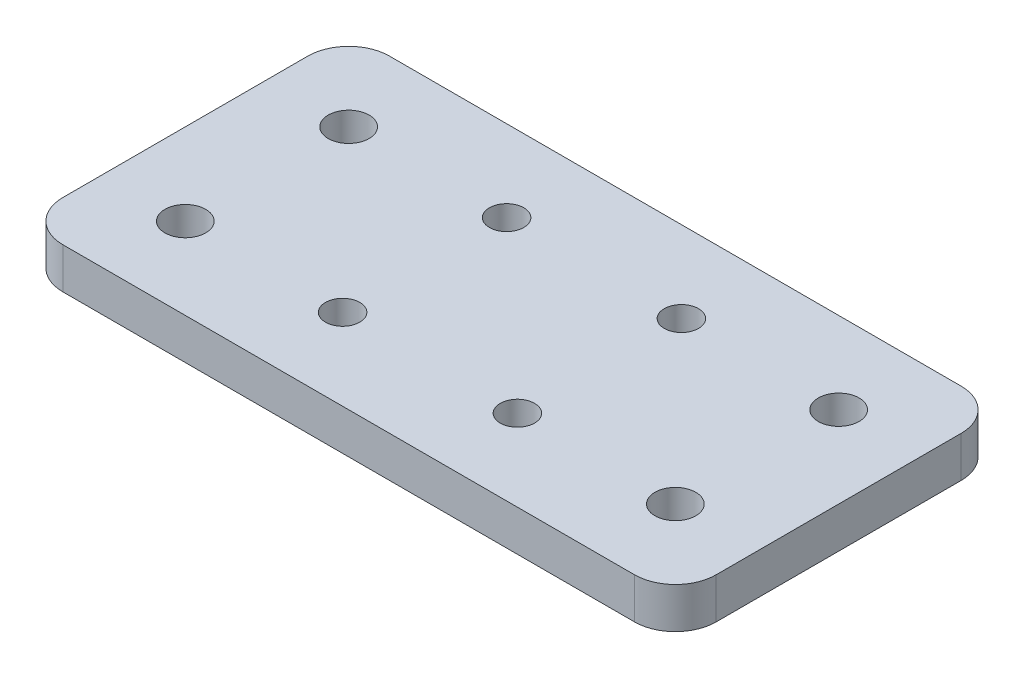
SolidWorks part; units mm, degrees
material "6061 Alloy"
ref_plane "Front Plane" through (0, 0, 0) normal (0, 0, 1) x (1, 0, 0)
ref_plane "Top Plane" through (0, 0, 0) normal (0, 1, 0) x (1, 0, 0)
ref_plane "Right Plane" through (0, 0, 0) normal (1, 0, 0) x (0, 0, -1)
sketch "Sketch1" plane through (0, 0, 0) normal (0, 1, 0) x (1, 0, 0)
  line L1 (-50.8, 25.4) -> (50.8, 25.4)
  line L2 (-50.8, 25.4) -> (-50.8, -25.4)
  line L3 (-50.8, -25.4) -> (50.8, -25.4)
  line L4 (50.8, 25.4) -> (50.8, -25.4)
  line L5 (-50.8, 25.4) -> (50.8, -25.4) construction
  line L6 (-50.8, -25.4) -> (50.8, 25.4) construction
  point P0 (0, 0)
  dimension "D1" = 50.8
  dimension "D2" = 101.6
extrude "Boss-Extrude1" add sketch "Sketch1" along normal blind 6.35
sketch "Sketch3" plane through (0, 0, 0) normal (0, -1, 0) x (1, 0, 0)
  line L0 (0, 0) -> (0, -20.7585) construction
  line L1 (1.5, 0) -> (-11.6006, 0) construction
  line L6 (50.8, -25.4) -> (-50.8, -25.4) construction
  line L7 (-50.8, 25.4) -> (50.8, 25.4) construction
  line L8 (-50.8, -25.4) -> (-50.8, 25.4) construction
  line L9 (50.8, 25.4) -> (50.8, -25.4) construction
  circle A0 centre (-38.1, 12.7) radius 3.175
  circle A1 centre (-38.1, -12.7) radius 3.175
  circle A2 centre (38.1, 12.7) radius 3.175
  circle A3 centre (38.1, -12.7) radius 3.175
  circle A4 centre (13.589, -12.75) radius 2.667
  circle A5 centre (-13.589, -12.75) radius 2.667
  circle A6 centre (13.589, 12.75) radius 2.667
  circle A7 centre (-13.589, 12.75) radius 2.667
  dimension "D1" = 25.4
  dimension "D4" = 50.8
  dimension "D5" = 13.589
  dimension "D6" = 13.589
  dimension "D7" = 13.589
  dimension "D8" = 13.589
  dimension "D9" = 12.75
  dimension "D10" = 12.75
  dimension "D11" = 12.75
  dimension "D13" = 5.334
  dimension "D3" = 50.8
  dimension "D14" = 5.334
  dimension "D15" = 5.334
  dimension "D16" = 5.334
  dimension "D17" = 6.35
  dimension "D18" = 6.35
  dimension "D19" = 6.35
  dimension "D20" = 6.35
  dimension "D21" = 12.7
  dimension "D22" = 12.7
  dimension "D23" = 12.7
  dimension "D24" = 12.7
  dimension "D26" = 12.7
  dimension "D27" = 12.7
  dimension "D28" = 12.7
  dimension "D2" = 25.4
  dimension "D12" = 12.75
  dimension "D25" = 12.7
extrude "Cut-Extrude2" cut sketch "Sketch3" against normal up to next
fillet "Fillet1" radius 6.35 4 edges at (-50.8, 3.175, -25.4) (50.8, 3.175, -25.4) (50.8, 3.175, 25.4) (-50.8, 3.175, 25.4)
sketch "Sketch4" plane through (0, 6.35, 0) normal (0, 1, 0) x (1, 0, 0)
  point P0 (38.1, 12.7)
  point P1 (13.589, 12.75)
sketch "Sketch6" plane through (0, 6.35, 0) normal (0, 1, 0) x (1, 0, 0)
  point P0 (0, 0)
